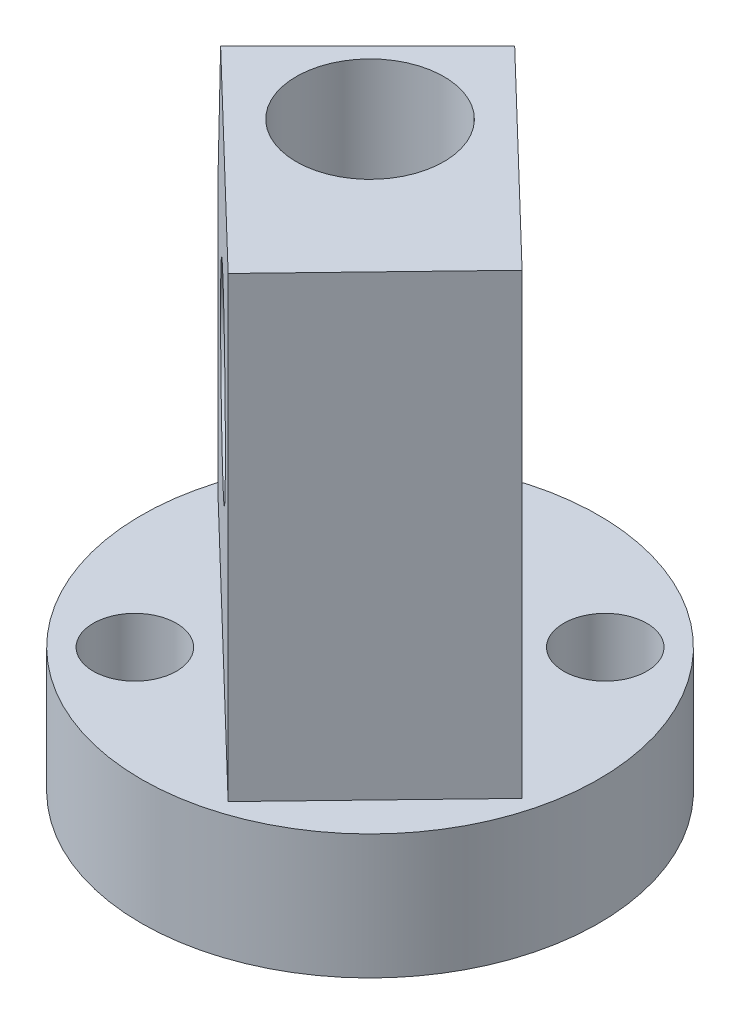
SolidWorks part; units mm, degrees
ref_plane "Plan de face" through (0, 0, 0) normal (0, 0, 1) x (1, 0, 0)
ref_plane "Plan de dessus" through (0, 0, 0) normal (0, 1, 0) x (1, 0, 0)
ref_plane "Plan de droite" through (0, 0, 0) normal (1, 0, 0) x (0, 0, -1)
ref_plane "Plan1" through (0, 0, 0) normal (0, 0, -1) x (-1, 0, 0)
sketch "Esquisse1" plane through (0, 0, 0) normal (0, 0, -1) x (-1, 0, 0)
  line L0 (-11, 0) -> (0, 0)
  line L1 (0, 0) -> (0, 6)
  line L2 (0, 6) -> (-11, 6)
  line L3 (-11, 6) -> (-11, 0)
  line L4 (0, 0) -> (0, 6) construction
revolve "Révolution1" add sketch "Esquisse1" angle 360 about L4
sketch "Esquisse2" plane through (0, 6, 0) normal (0, 1, 0) x (-1, 0, 0)
  line L0 (-9.9516, 2.6394) -> (-3.0164, 9.8438)
  line L1 (-3.0164, 9.8438) -> (10.0888, -2.7715)
  line L2 (10.0888, -2.7715) -> (3.0164, -9.8438)
  line L3 (3.0164, -9.8438) -> (-9.9516, 2.6394)
extrude "Boss.-Extru.1" add sketch "Esquisse2" along normal blind 22
hole_wizard "Diamètre du perçage Ø7.1 (7.1)1" positions "Esquisse4" profile "Esquisse3" hole size "Ø7.1" standard "Ansi Metric"
sketch "Esquisse4" plane through (0, 28, 0) normal (0, 1, 0) x (1, 0, 0)
  point P0 (0, 0)
sketch "Esquisse3" plane through (0, 28, 0) normal (1, 0, 0) x (0, 0, 1)
  line L0 (0, 0) -> (0, 6)
  line L1 (0, 6) -> (3.55, 6)
  line L2 (3.55, 6) -> (3.55, 0)
  line L5 (3.55, 0) -> (0, 0)
  line L10 (0, 6) -> (-3.55, 6) construction
  line L11 (0, -6.35) -> (0, 107.95) construction
  dimension "Diamètre du perçage" = 7.1
  dimension "Profondeur du perçage" = 6
  dimension "Angle de pointe" = 180
hole_wizard "Diamètre du perçage Ø8.5 (8.5)1" positions "Esquisse6" profile "Esquisse5" hole size "Ø8.5" standard "Ansi Metric" end condition through all
sketch "Esquisse6" plane through (-3.4676, 0, 3.6022) normal (-0.6935, 0, 0.7204) x (0.7204, 0, 0.6935)
  point P0 (-0.1905, 17)
sketch "Esquisse5" plane through (-3.6048, 17, 3.4701) normal (0, 1, 0) x (0.7204, 0, 0.6935)
  line L0 (0, 0) -> (0, 20.5535)
  line L1 (0, 20.5535) -> (4.25, 20.5535)
  line L2 (4.25, 20.5535) -> (4.25, 0)
  line L5 (4.25, 0) -> (0, 0)
  line L11 (0, -6.35) -> (0, 107.95) construction
  dimension "Diamètre du perçage jusqu'au prochain" = 8.5
  dimension "Profondeur du perçage jusqu'au prochain" = 20.5535
hole_wizard "Chambrage pour vis à tête hexagonale M21" positions "Esquisse8" profile "Esquisse7" counterbore size "M2" standard "Ansi Metric"
sketch "Esquisse8" plane through (0, 6, 0) normal (0, 1, 0) x (1, 0, 0)
  point P0 (5.6569, 5.6569)
  point P1 (-5.6569, -5.6569)
sketch "Esquisse7" plane through (5.6569, 6, -5.6569) normal (1, 0, 0) x (0, 0, 1)
  line L0 (0, 0) -> (0, 6)
  line L1 (0, 6) -> (1.25, 6)
  line L3 (1.25, 6) -> (1.25, 4.5)
  line L4 (1.25, 4.5) -> (2, 4.5)
  line L5 (2, 4.5) -> (2, 0)
  line L7 (2, 0) -> (0, 0)
  line L11 (0, -6.35) -> (0, 107.95) construction
  dimension "Diamètre du perçage jusqu'au prochain" = 2.5
  dimension "Profondeur du perçage jusqu'au prochain" = 6
  dimension "Diamètre du chambrage" = 4
  dimension "Profondeur du chambrage" = 4.5
hole_wizard "Diamètre du perçage Ø8.0 (8)1" positions "Esquisse10" profile "Esquisse9" hole size "Ø8.0" standard "Ansi Metric"
sketch "Esquisse10" plane through (0, 0, 0) normal (0, -1, 0) x (-1, 0, 0)
  point P0 (0, 0)
sketch "Esquisse9" plane through (0, 0, 0) normal (1, 0, 0) x (0, 0, -1)
  line L0 (0, 0) -> (0, 6)
  line L1 (0, 6) -> (4, 2)
  line L2 (4, 2) -> (4, 0)
  line L5 (4, 0) -> (0, 0)
  line L10 (0, 6) -> (-4, 2) construction
  line L11 (0, -6.35) -> (0, 107.95) construction
  dimension "Diamètre du perçage" = 8
  dimension "Profondeur du perçage" = 2
  dimension "Angle de pointe" = 90
chamfer "Chanfrein1" distance 9 angle 28 1 edges at (-6.5526, 28, -6.3077)
